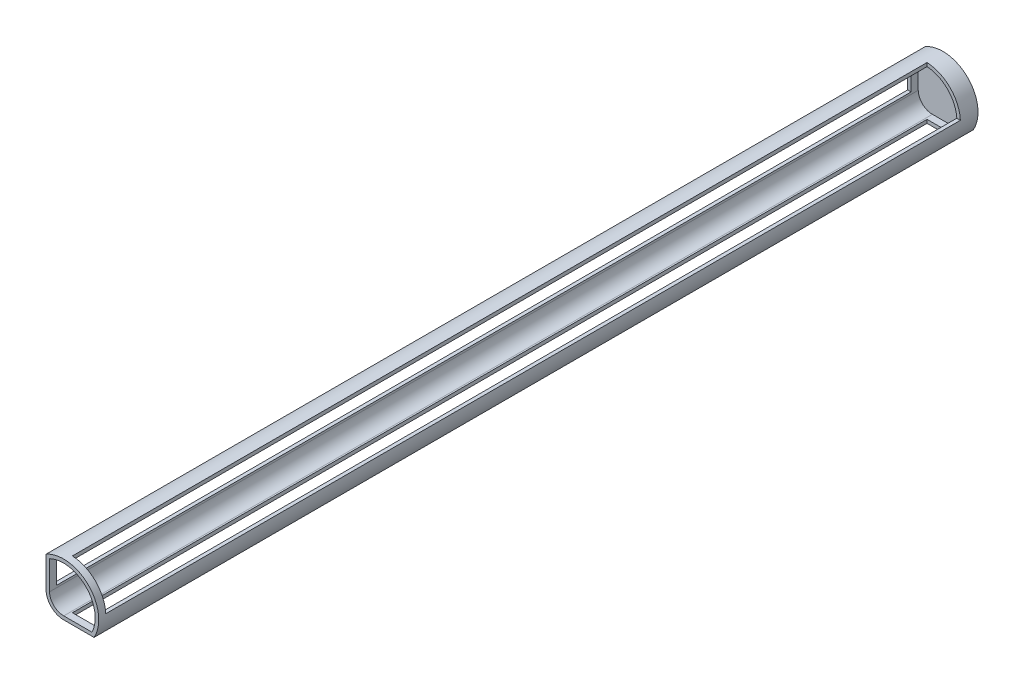
SolidWorks part; units mm, degrees
ref_plane "Plano frontal" through (0, 0, 0) normal (0, 0, 1) x (1, 0, 0)
ref_plane "Plano superior" through (0, 0, 0) normal (0, 1, 0) x (1, 0, 0)
ref_plane "Plano direito" through (0, 0, 0) normal (1, 0, 0) x (0, 0, -1)
sketch "Esboço2" plane through (0, 0, 0) normal (0, 0, 1) x (1, 0, 0)
  line L0 (-7.5, 6.1603) -> (-7.5, -2.5)
  line L1 (6.1603, -7.5) -> (-2.5, -7.5)
  arc A0 (-2.5, -7.5) -> (-7.5, -2.5) centre (-2.5, -2.5) cw
  arc A1 (-7.5, 6.1603) -> (6.1603, -7.5) centre (-2.5, -2.5) cw
extrude "Ressalto-extrusão1" add sketch "Esboço2" along normal blind 250
sketch "Esboço3" plane through (0, 0, 250) normal (0, 0, 1) x (1, 0, 0)
  line L5 (-6.5, 5.5623) -> (-6.5, -2.5951)
  line L8 (0.7966, -6.5) -> (5.5623, -6.5)
  line L9 (0.7966, -6.5) -> (-2.4581, -6.5)
  arc A1 (-6.5, 5.5623) -> (5.5623, -6.5) centre (-2.5277, -2.5277) cw
  arc A3 (-6.5, -2.5951) -> (-2.4581, -6.5) centre (-2.5266, -2.5266) ccw
extrude "Corte-extrusão1" cut sketch "Esboço3" against normal blind 247
sketch "Esboço4" plane through (0, -7.5, 0) normal (0, -1, 0) x (1, 0, 0)
  line L0 (-2.5, 0) -> (6.1603, 0) construction
  line L1 (-2.5, 250) -> (-2.5, 0) construction
  line L2 (-2, 248) -> (5.5, 248)
  line L3 (-2, 248) -> (-2, 5)
  line L4 (-2, 5) -> (5.5, 5)
  line L5 (5.5, 248) -> (5.5, 5)
  line L6 (-2, 248) -> (5.5, 5) construction
  line L7 (-2, 5) -> (5.5, 248) construction
  line L8 (-2.5, 250) -> (6.1603, 250) construction
  point P0 (1.75, 126.5)
  dimension "D1" = 7.5
  dimension "D2" = 5
  dimension "D3" = 0.5
  dimension "D4" = 2
extrude "Corte-extrusão2" cut sketch "Esboço4" against normal blind 245
sketch "Esboço5" plane through (-7.5, 0, 0) normal (-1, 0, 0) x (0, 0, 1)
  line L1 (5, 5.5) -> (248, 5.5)
  line L2 (5, 5.5) -> (5, -2)
  line L3 (5, -2) -> (248, -2)
  line L4 (248, 5.5) -> (248, -2)
  line L5 (5, 5.5) -> (248, -2) construction
  line L6 (5, -2) -> (248, 5.5) construction
  line L7 (250, -2.5) -> (0, -2.5) construction
  line L8 (0, 6.1603) -> (0, -2.5) construction
  point P0 (126.5, 1.75)
  dimension "D1" = 243
  dimension "D2" = 7.5
  dimension "D3" = 0.5
  dimension "D4" = 5
extrude "Corte-extrusão3" cut sketch "Esboço5" against normal blind 245
